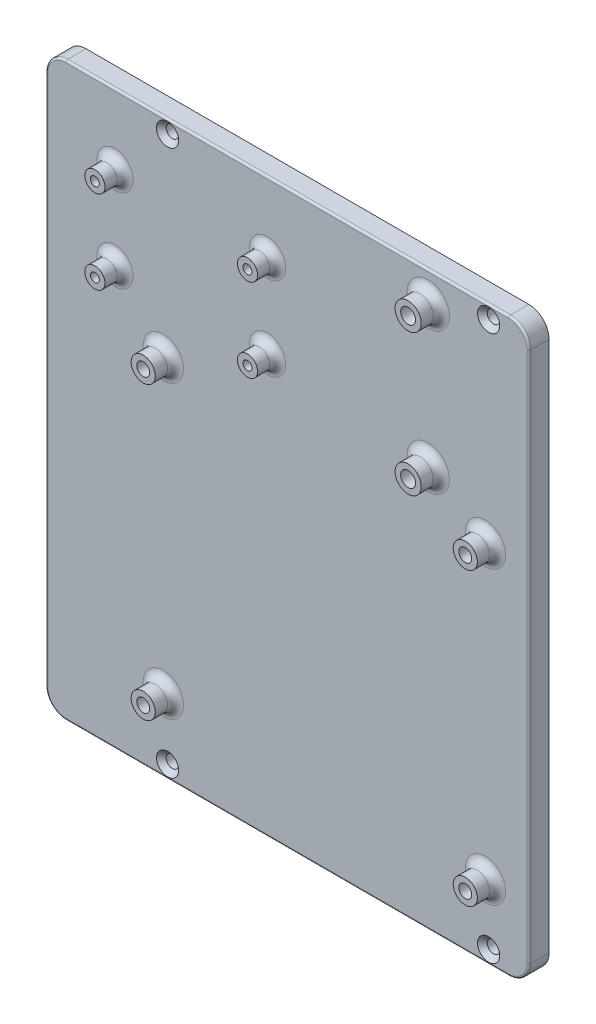
SolidWorks part; units mm, degrees
ref_plane "Plano frontal" through (0, 0, 0) normal (0, 0, 1) x (1, 0, 0)
ref_plane "Plano superior" through (0, 0, 0) normal (0, 1, 0) x (1, 0, 0)
ref_plane "Plano direito" through (0, 0, 0) normal (1, 0, 0) x (0, 0, -1)
sketch "Esboço1" plane through (0, 0, 0) normal (0, 0, 1) x (1, 0, 0)
  line L1 (0, -5) -> (110, -5)
  line L2 (-5, 0) -> (-5, 132)
  line L3 (0, 137) -> (110, 137)
  line L4 (115, 0) -> (115, 132)
  arc A0 (-5, 0) -> (0, -5) centre (0, 0) ccw
  arc A1 (0, 137) -> (-5, 132) centre (0, 132) ccw
  arc A2 (115, 132) -> (110, 137) centre (110, 132) ccw
  arc A3 (110, -5) -> (115, 0) centre (110, 0) ccw
  dimension "D3" = 10
  dimension "D1" = 142
  dimension "D2" = 120
extrude "Ressalto-extrusão1" add sketch "Esboço1" along normal blind 5
fillet "Filete2" radius 0.5 8 edges at (55, -5, 5) (-3.5355, -3.5355, 5) (-5, 66, 5) (-3.5355, 135.5355, 5) (55, 137, 5) (113.5355, 135.5355, 5) (115, 66, 5) (113.5355, -3.5355, 5)
sketch "Esboço6" plane through (0, 0, 5) normal (0, 0, 1) x (1, 0, 0)
  line L0 (90, 112) -> (146.9554, 112) construction
  line L1 (18, 88) -> (110, 88) construction
  line L2 (18, 88) -> (18, 5) construction
  line L3 (18, 5) -> (110, 5) construction
  line L4 (110, 88) -> (110, 5) construction
  line L5 (10, 96.5) -> (52.3, 96.5) construction
  line L6 (10, 96.5) -> (10, 122) construction
  line L7 (10, 122) -> (52.3, 122) construction
  line L8 (52.3, 96.5) -> (52.3, 122) construction
  line L9 (90, 112) -> (90, 134.05) construction
  line L10 (31.15, 96.5) -> (31.15, 122) construction
  line L11 (31.15, 109.25) -> (52.3, 109.25) construction
  line L12 (0, 137) -> (110, 137) construction
  line L13 (115, 132) -> (115, 0) construction
  line L15 (110, -5) -> (0, -5) construction
  line L16 (115, 0) -> (115, 132) construction
  line L19 (-5, 132) -> (-5, 0) construction
  circle A0 centre (90, 112) radius 22.05 construction
  circle A1 centre (24.2, 85.2) radius 3
  circle A2 centre (104.2, 85.2) radius 3
  circle A3 centre (104.2, 12.9) radius 3
  circle A4 centre (24.2, 12.9) radius 3
  circle A5 centre (90, 129.55) radius 3.25
  circle A6 centre (90, 94.45) radius 3.25
  circle A7 centre (50.1, 98.9) radius 2.5
  circle A8 centre (12.2, 119.6) radius 2.5
  circle A9 centre (12.2, 98.9) radius 2.5
  circle A10 centre (50.1, 119.6) radius 2.5
  dimension "D3" = 44.1
  dimension "D10" = 4.5
  dimension "D11" = 6.5
  dimension "D12" = 6
  dimension "D13" = 5
  dimension "D16" = 25
  dimension "D1" = 92
  dimension "D2" = 83
  dimension "D4" = 42.3
  dimension "D5" = 25.5
  dimension "D6" = 6.2
  dimension "D7" = 2.8
  dimension "D8" = 72.3
  dimension "D9" = 80
  dimension "D14" = 2.4
  dimension "D15" = 2.2
  dimension "D17" = 5
  dimension "D18" = 10
  dimension "D19" = 25
  dimension "D20" = 15
  dimension "D21" = 15
extrude "Ressalto-extrusão3" add sketch "Esboço6" along normal blind 5
hole_wizard "Furo com folga de M21" positions "Esboço10" profile "Esboço9" hole size "M2" standard "ISO" end condition through all
sketch "Esboço10" plane through (0, 0, 10) normal (0, 0, 1) x (1, 0, 0)
  point P0 (12.2, 119.6)
  point P3 (12.2, 98.9)
  point P6 (50.1, 119.6)
  point P9 (50.1, 98.9)
sketch "Esboço9" plane through (12.2, 119.6, 10) normal (1, 0, 0) x (0, -1, 0)
  line L0 (0, 0) -> (0, 10)
  line L1 (0, 10) -> (1.1, 10)
  line L2 (1.1, 10) -> (1.1, 0)
  line L5 (1.1, 0) -> (0, 0)
  line L11 (0, -6.35) -> (0, 107.95) construction
  dimension "Thru Hole Dia." = 2.2
  dimension "Thru Hole Depth" = 10
hole_wizard "Furo com folga de M31" positions "Esboço12" profile "Esboço11" hole size "M3" standard "ISO" end condition through all
sketch "Esboço12" plane through (0, 0, 10) normal (0, 0, 1) x (1, 0, 0)
  point P0 (24.2, 85.2)
  point P3 (24.2, 12.9)
  point P6 (104.2, 12.9)
  point P9 (104.2, 85.2)
sketch "Esboço11" plane through (24.2, 85.2, 10) normal (1, 0, 0) x (0, -1, 0)
  line L0 (0, 0) -> (0, 10)
  line L1 (0, 10) -> (1.6, 10)
  line L2 (1.6, 10) -> (1.6, 0)
  line L5 (1.6, 0) -> (0, 0)
  line L11 (0, -6.35) -> (0, 107.95) construction
  dimension "Thru Hole Dia." = 3.2
  dimension "Thru Hole Depth" = 10
hole_wizard "Furo com folga de M3.51" positions "Esboço14" profile "Esboço13" hole size "M3.5" standard "ISO" end condition through all
sketch "Esboço14" plane through (0, 0, 10) normal (0, 0, 1) x (1, 0, 0)
  point P0 (90, 129.55)
  point P3 (90, 94.45)
sketch "Esboço13" plane through (90, 129.55, 10) normal (1, 0, 0) x (0, -1, 0)
  line L0 (0, 0) -> (0, 10)
  line L1 (0, 10) -> (1.85, 10)
  line L2 (1.85, 10) -> (1.85, 0)
  line L5 (1.85, 0) -> (0, 0)
  line L11 (0, -6.35) -> (0, 107.95) construction
  dimension "Thru Hole Dia." = 3.7
  dimension "Thru Hole Depth" = 10
sketch "Esboço15" plane through (0, 0, 5) normal (0, 0, 1) x (1, 0, 0)
  line L0 (-4.5, 66) -> (-40.2581, 66) construction
  line L1 (25.25, 133.75) -> (105, 133.75) construction
  line L2 (25.25, 133.75) -> (25.25, -1.75) construction
  line L3 (25.25, -1.75) -> (105, -1.75) construction
  line L4 (105, 133.75) -> (105, -1.75) construction
  line L5 (-4.5, 132) -> (-4.5, 0) construction
  line L7 (115, 132) -> (115, 0) construction
  dimension "D1" = 135.5
  dimension "D2" = 79.75
  dimension "D3" = 10
hole_wizard "Escareado para parafuso com cabeça escareada chata de M2.51" positions "Esboço17" profile "Esboço16" countersink size "M2.5" standard "ISO" end condition through all
sketch "Esboço17" plane through (0, 0, 5) normal (0, 0, 1) x (1, 0, 0)
  point P0 (25.25, 133.75)
  point P3 (105, 133.75)
  point P6 (105, -1.75)
  point P9 (25.25, -1.75)
sketch "Esboço16" plane through (25.25, 133.75, 5) normal (1, 0, 0) x (0, -1, 0)
  line L0 (0, 0) -> (0, 5)
  line L1 (0, 5) -> (1.55, 5)
  line L2 (1.55, 5) -> (1.55, 1.2)
  line L3 (1.55, 1.2) -> (2.75, 0)
  line L5 (2.75, 0) -> (0, 0)
  line L6 (-1.55, 1.2) -> (-2.75, 0) construction
  line L11 (0, -6.35) -> (0, 107.95) construction
  dimension "Thru Hole Dia." = 3.1
  dimension "Thru Hole Depth" = 5
  dimension "Near C'Sink Dia." = 5.5
  dimension "Near C'Sink Angle" = 90
fillet "Filete3" radius 2 10 edges at (107.2, 12.9, 5) (27.2, 12.9, 5) (107.2, 85.2, 5) (93.25, 129.55, 5) (93.25, 94.45, 5) (27.2, 85.2, 5) (14.7, 98.9, 5) (9.7, 119.6, 5) (47.6, 98.9, 5) (52.6, 119.6, 5)
